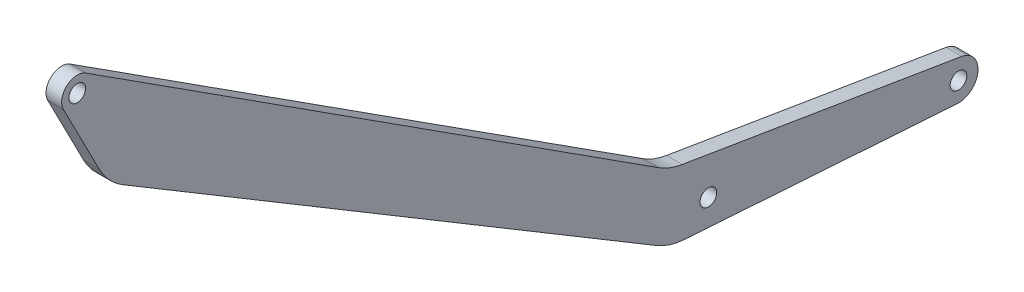
SolidWorks part; units mm, degrees
ref_plane "Front Plane" through (0, 0, 0) normal (0, 0, 1) x (1, 0, 0)
ref_plane "Top Plane" through (0, 0, 0) normal (0, 1, 0) x (1, 0, 0)
ref_plane "Right Plane" through (0, 0, 0) normal (1, 0, 0) x (0, 0, -1)
ref_plane "Plane1" through (-76.9133, 0, 0) normal (1, 0, 0) x (0, 0, -1)
sketch "Sketch1" plane through (-76.9133, 0, 0) normal (1, 0, 0) x (0, 0, -1)
  line L0 (535.7661, 896.8306) -> (535.7661, 915.8806) construction
  line L1 (434.1661, 906.5188) -> (434.1661, 925.5688) construction
  line L2 (177.8, 1090.4307) -> (434.1661, 925.5688) construction
  line L3 (139.7, 1090.4307) -> (177.8, 1090.4307) construction
  line L4 (535.7661, 896.8306) -> (535.7661, 915.8806) construction
  line L5 (434.1661, 906.5188) -> (434.1661, 925.5688) construction
  line L6 (177.8, 1090.4307) -> (434.1661, 925.5688) construction
  line L7 (139.7, 1090.4307) -> (177.8, 1090.4307) construction
  line L8 (535.2188, 907.962) -> (418.2911, 916.0438)
  line L9 (537.0595, 923.712) -> (418.2911, 943.3273)
  line L10 (172.155, 1087.5226) -> (190.1159, 1052.6585)
  line L11 (190.1159, 1052.6585) -> (418.2911, 916.0438)
  line L12 (418.2911, 943.3273) -> (181.2346, 1095.7717)
  circle A0 centre (177.8, 1090.4307) radius 3.3782
  circle A1 centre (434.1661, 925.5688) radius 3.3782
  circle A2 centre (535.7661, 915.8806) radius 3.3782
  arc A3 (535.2188, 907.962) -> (537.0595, 923.712) centre (535.7661, 915.8806) ccw
  arc A5 (181.2346, 1095.7717) -> (172.155, 1087.5226) centre (177.8, 1090.4307) ccw
  arc A6 (537.0595, 923.712) -> (535.2188, 907.962) centre (535.7661, 915.8806) ccw construction
  arc A7 (172.155, 1087.5226) -> (183.141, 1086.9961) centre (177.8, 1090.4307) ccw construction
  arc A8 (183.141, 1086.9961) -> (181.2346, 1095.7717) centre (177.8, 1090.4307) ccw construction
  spline S0 degree 3 poles (935.6767, 939.7163) (940.3147, 942.1548) (935.2529, 940.0507) (930.9716, 938.764) (920.6916, 935.461) (907.9553, 931.9087) (891.2949, 927.4743) (871.5218, 922.6042) (848.5739, 917.4165) (822.7695, 912.1503) (794.3904, 907.0475) (763.8436, 902.4482) (731.6326, 898.5836) (698.2942, 895.5048) (664.3294, 893.3038) (630.2914, 892.1587) (596.9177, 892.4579) (565.0805, 894.155) (535.5455, 896.7257) (508.8897, 899.7641) (485.4664, 902.8148) (465.3261, 905.1664) (448.3721, 906.4646) (434.4368, 906.7165) (423.4463, 905.9074) (416.5733, 904.5379) (412.9407, 903.1204) (411.5732, 902.4729) (410.4746, 901.8174) (409.7947, 901.3358) (409.3397, 900.9203) (409.0422, 900.6195) (408.7846, 900.3039) (408.5873, 899.9553) (408.4178, 899.5844) (408.2374, 899.0451) (408.051, 898.3239) (407.9116, 897.2265) (407.8599, 894.9991) (408.6865, 890.8402) (411.376, 884.946) (416.2539, 878.2548) (423.1327, 871.4111) (431.9816, 864.5947) (442.7539, 857.9825) (455.382, 851.7275) (469.765, 845.9615) (485.7865, 840.8065) (503.3041, 836.37) (522.1586, 832.7575) (542.1676, 830.0521) (563.1459, 828.3505) (584.9266, 827.7965) (607.3492, 828.4639) (630.2782, 830.4035) (653.5854, 833.657) (677.1845, 838.2437) (700.9897, 844.1113) (724.9284, 850.9153) (748.8232, 858.3979) (772.4019, 866.3681) (795.3921, 874.6046) (817.5075, 882.9123) (838.4515, 891.1278) (857.9391, 899.0809) (875.6775, 906.6433) (891.4161, 913.7156) (904.9213, 920.2497) (916.21, 926.5709) (924.8872, 932.3286) (932.3848, 937.3638) (935.6767, 939.7163) (940.3147, 942.1548) (935.2529, 940.0507) knots -0.014576 -0.006911 -0.001813 0 0.001841 0.007308 0.016237 0.028456 0.043801 0.062126 0.08324 0.106896 0.132817 0.160613 0.189791 0.219873 0.250457 0.281127 0.311257 0.339999 0.366671 0.390812 0.411995 0.430069 0.445224 0.457619 0.467425 0.474786 0.47628 0.477884 0.47884 0.479711 0.480113 0.480492 0.480846 0.481203 0.481564 0.48194 0.482727 0.483559 0.484903 0.488692 0.494806 0.502149 0.510796 0.520764 0.532062 0.544666 0.558541 0.573612 0.589803 0.60701 0.625107 0.643967 0.663469 0.683551 0.704142 0.725196 0.74668 0.768633 0.790977 0.813463 0.835827 0.857772 0.879003 0.899228 0.918151 0.935487 0.950987 0.964428 0.975828 0.985424 0.993089 0.998187 1 1.001841 1.007308 1.016237 only from (939.324, 941.6889) to (939.324, 941.6889) construction
  spline S1 degree 3 poles (935.6767, 939.7163) (940.3147, 942.1548) (935.2529, 940.0507) (930.9716, 938.764) (920.6916, 935.461) (907.9553, 931.9087) (891.2949, 927.4743) (871.5218, 922.6042) (848.5739, 917.4165) (822.7695, 912.1503) (794.3904, 907.0475) (763.8436, 902.4482) (731.6326, 898.5836) (698.2942, 895.5048) (664.3294, 893.3038) (630.2914, 892.1587) (596.9177, 892.4579) (565.0805, 894.155) (535.5455, 896.7257) (508.8897, 899.7641) (485.4664, 902.8148) (465.3261, 905.1664) (448.3721, 906.4646) (434.4368, 906.7165) (423.4463, 905.9074) (416.5733, 904.5379) (412.9407, 903.1204) (411.5732, 902.4729) (410.4746, 901.8174) (409.7947, 901.3358) (409.3397, 900.9203) (409.0422, 900.6195) (408.7846, 900.3039) (408.5873, 899.9553) (408.4178, 899.5844) (408.2374, 899.0451) (408.051, 898.3239) (407.9116, 897.2265) (407.8599, 894.9991) (408.6865, 890.8402) (411.376, 884.946) (416.2539, 878.2548) (423.1327, 871.4111) (431.9816, 864.5947) (442.7539, 857.9825) (455.382, 851.7275) (469.765, 845.9615) (485.7865, 840.8065) (503.3041, 836.37) (522.1586, 832.7575) (542.1676, 830.0521) (563.1459, 828.3505) (584.9266, 827.7965) (607.3492, 828.4639) (630.2782, 830.4035) (653.5854, 833.657) (677.1845, 838.2437) (700.9897, 844.1113) (724.9284, 850.9153) (748.8232, 858.3979) (772.4019, 866.3681) (795.3921, 874.6046) (817.5075, 882.9123) (838.4515, 891.1278) (857.9391, 899.0809) (875.6775, 906.6433) (891.4161, 913.7156) (904.9213, 920.2497) (916.21, 926.5709) (924.8872, 932.3286) (932.3848, 937.3638) (935.6767, 939.7163) (940.3147, 942.1548) (935.2529, 940.0507) knots -0.014576 -0.006911 -0.001813 0 0.001841 0.007308 0.016237 0.028456 0.043801 0.062126 0.08324 0.106896 0.132817 0.160613 0.189791 0.219873 0.250457 0.281127 0.311257 0.339999 0.366671 0.390812 0.411995 0.430069 0.445224 0.457619 0.467425 0.474786 0.47628 0.477884 0.47884 0.479711 0.480113 0.480492 0.480846 0.481203 0.481564 0.48194 0.482727 0.483559 0.484903 0.488692 0.494806 0.502149 0.510796 0.520764 0.532062 0.544666 0.558541 0.573612 0.589803 0.60701 0.625107 0.643967 0.663469 0.683551 0.704142 0.725196 0.74668 0.768633 0.790977 0.813463 0.835827 0.857772 0.879003 0.899228 0.918151 0.935487 0.950987 0.964428 0.975828 0.985424 0.993089 0.998187 1 1.001841 1.007308 1.016237 only from (939.324, 941.6889) to (939.324, 941.6889) construction
  point P11 (0, 0)
  point P16 (450.535, 937.686)
  point P21 (0, 0)
  point P22 (183.4713, 1075.4591)
  point P23 (439.209, 952.0947)
  point P24 (193.8003, 1048.4044)
  point P25 (434.1661, 933.2432)
  point P26 (0, 0)
  point P27 (416.7468, 941.6889)
  point P28 (418.2911, 913.8144)
  dimension "D1" = 6.7564
  dimension "D2" = 6.7564
  dimension "D3" = 6.7564
  dimension "D4" = 15.875
  dimension "D5" = 30
  dimension "D6" = 12.7
  dimension "D7" = 148.166
  dimension "D8" = 15.875
  dimension "D9" = 9.525
extrude "Boss-Extrude1" add sketch "Sketch1" along normal mid plane 6.35
fillet "Fillet1" radius 25.4 3 edges at (-76.9133, 1052.6585, -190.1159) (-76.9133, 943.3273, -418.2911) (-76.9133, 916.0438, -418.2911)
